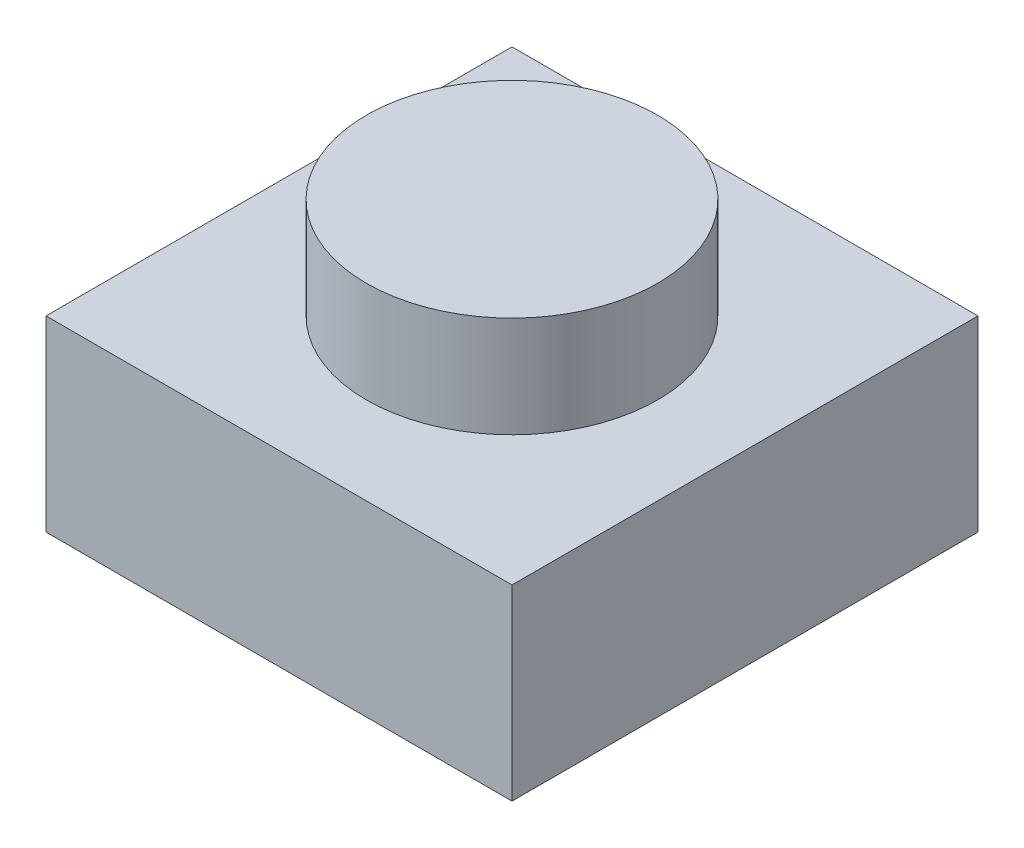
SolidWorks part; units mm, degrees
ref_plane "Front Plane" through (0, 0, 0) normal (0, 0, 1) x (1, 0, 0)
ref_plane "Top Plane" through (0, 0, 0) normal (0, 1, 0) x (1, 0, 0)
ref_plane "Right Plane" through (0, 0, 0) normal (1, 0, 0) x (0, 0, -1)
sketch "Sketch3" plane through (0, 0, 0) normal (0, 1, 0) x (1, 0, 0)
  line L1 (-3.92, 3.92) -> (3.92, 3.92)
  line L2 (-3.92, 3.92) -> (-3.92, -3.92)
  line L3 (-3.92, -3.92) -> (3.92, -3.92)
  line L4 (3.92, 3.92) -> (3.92, -3.92)
  line L5 (-3.92, 3.92) -> (3.92, -3.92) construction
  line L6 (-3.92, -3.92) -> (3.92, 3.92) construction
  point P0 (0, 0)
  dimension "D1" = 7.84
  dimension "D2" = 7.84
extrude "Boss-Extrude1" add sketch "Sketch3" against normal blind 3.15
sketch "Sketch4" plane through (0, 0, 0) normal (0, 1, 0) x (1, 0, 0)
  circle A0 centre (0, 0) radius 2.45
  dimension "D1" = 4.9
extrude "Boss-Extrude2" add sketch "Sketch4" along normal blind 1.7
shell "Shell1" thickness 1.5
